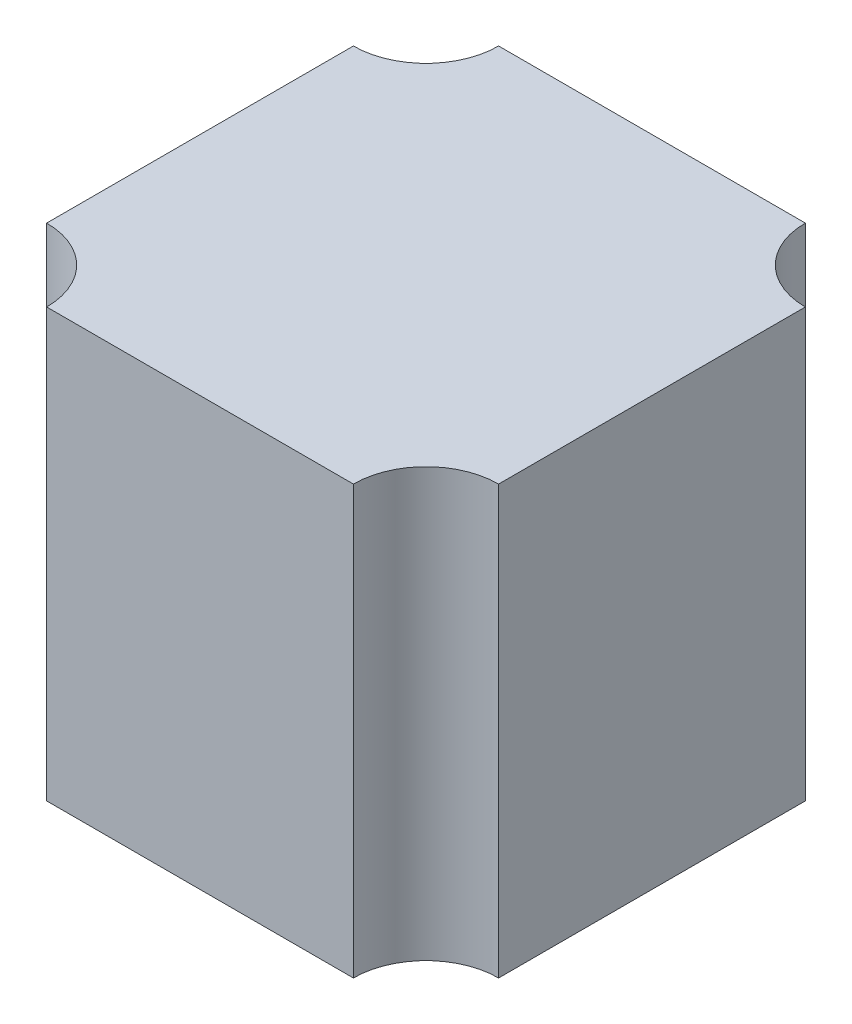
SolidWorks part; units mm, degrees
material "1060 Alloy"
ref_plane "Front Plane" through (0, 0, 0) normal (0, 0, 1) x (1, 0, 0)
ref_plane "Top Plane" through (0, 0, 0) normal (0, 1, 0) x (1, 0, 0)
ref_plane "Right Plane" through (0, 0, 0) normal (1, 0, 0) x (0, 0, -1)
sketch "Sketch1" plane through (0, 0, 0) normal (0, 1, 0) x (1, 0, 0)
  line L1 (-19, 28) -> (19, 28)
  line L2 (-28, 19) -> (-28, -19)
  line L3 (-19, -28) -> (19, -28)
  line L4 (28, 19) -> (28, -19)
  line L5 (-21.636, 21.636) -> (21.636, -21.636) construction
  line L6 (-21.636, -21.636) -> (21.636, 21.636) construction
  arc A0 (-28, 19) -> (-19, 28) centre (-28, 28) ccw
  arc A1 (19, 28) -> (28, 19) centre (28, 28) ccw
  arc A2 (28, -19) -> (19, -28) centre (28, -28) ccw
  arc A3 (-19, -28) -> (-28, -19) centre (-28, -28) ccw
  point P0 (0, 0)
  dimension "D3" = 18
  dimension "D1" = 56
  dimension "D2" = 56
extrude "Boss-Extrude1" add sketch "Sketch1" along normal blind 53
